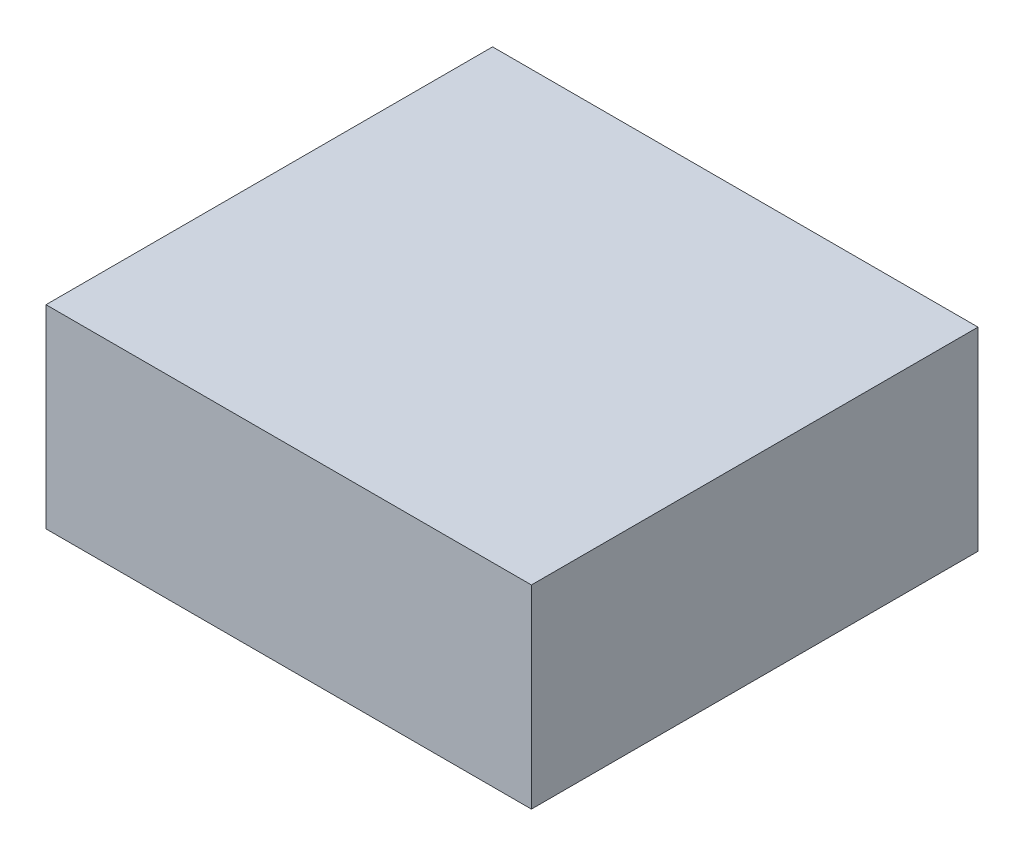
SolidWorks part; units mm, degrees
ref_plane "Front Plane" through (0, 0, 0) normal (0, 0, 1) x (1, 0, 0)
ref_plane "Top Plane" through (0, 0, 0) normal (0, 1, 0) x (1, 0, 0)
ref_plane "Right Plane" through (0, 0, 0) normal (1, 0, 0) x (0, 0, -1)
sketch "Sketch1" plane through (0, 0, 0) normal (0, 1, 0) x (1, 0, 0)
  line L1 (0, 0) -> (2.5, 0)
  line L2 (0, 0) -> (0, -2.3)
  line L3 (0, -2.3) -> (2.5, -2.3)
  line L4 (2.5, 0) -> (2.5, -2.3)
  dimension "D1" = 2.5
  dimension "D2" = 2.3
extrude "Boss-Extrude1" add sketch "Sketch1" along normal blind 1
